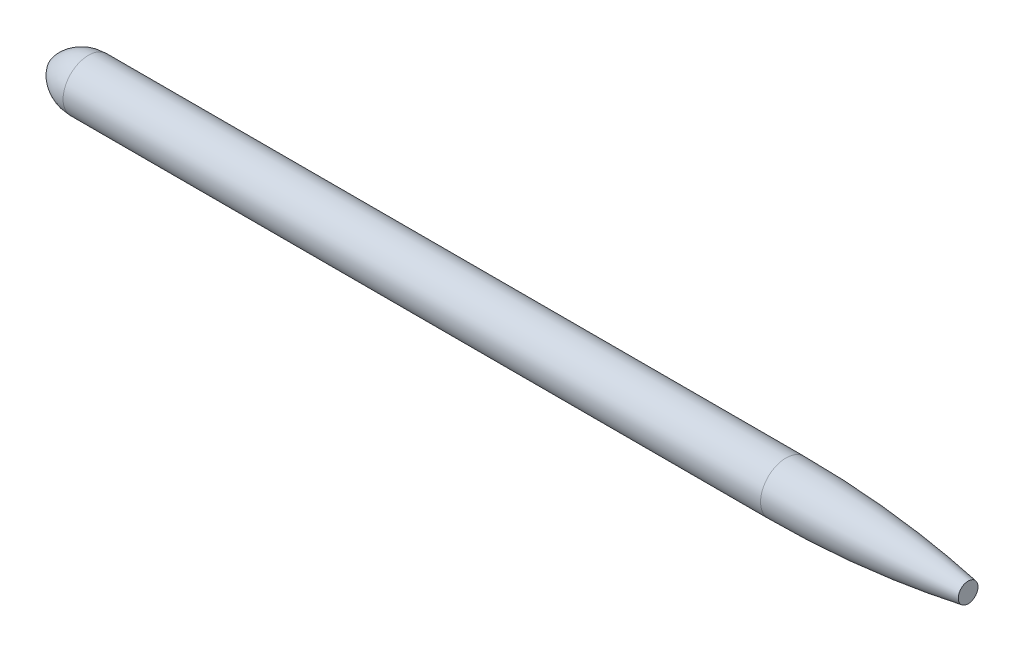
SolidWorks part; units mm, degrees
ref_plane "Front Plane" through (0, 0, 0) normal (0, 0, 1) x (1, 0, 0)
ref_plane "Top Plane" through (0, 0, 0) normal (0, 1, 0) x (1, 0, 0)
ref_plane "Right Plane" through (0, 0, 0) normal (1, 0, 0) x (0, 0, -1)
sketch "rootSketch" plane through (0, 0, 0) normal (0, 1, 0) x (1, 0, 0)
  line L0 (0, 0) -> (12000, 0) construction
  line L1 (270, -180) -> (270, 180) construction
  line L2 (0, 0) -> (6500, 0)
  line L3 (270, -180) -> (5210, -180)
  line L4 (6500, -70) -> (6500, 0)
  arc A0 (5210, -180) -> (6500, -70) centre (5210, 7439.0909) ccw
  arc A1 (270, -180) -> (0, 0) centre (270, 112.5) cw
  point P5 (270, 0)
  dimension "rootMaxThickness" = 360
  dimension "D1" = 6500
  dimension "D2" = 270
  dimension "D3" = 1290
  dimension "D4" = 70
revolve "Revolve1" add sketch "rootSketch" angle 360 about L0
ref_plane "Plane1" through (5330, 0, 0) normal (1, 0, 0) x (0, 0, -1)
equation "\"chord\"= 6.5"
equation "\"NACAairfoil\"= 0006"
equation "\"tailCutoffPercentage\"= 0.18"
equation "\"D1@rootSketch\"=\"chord\""
